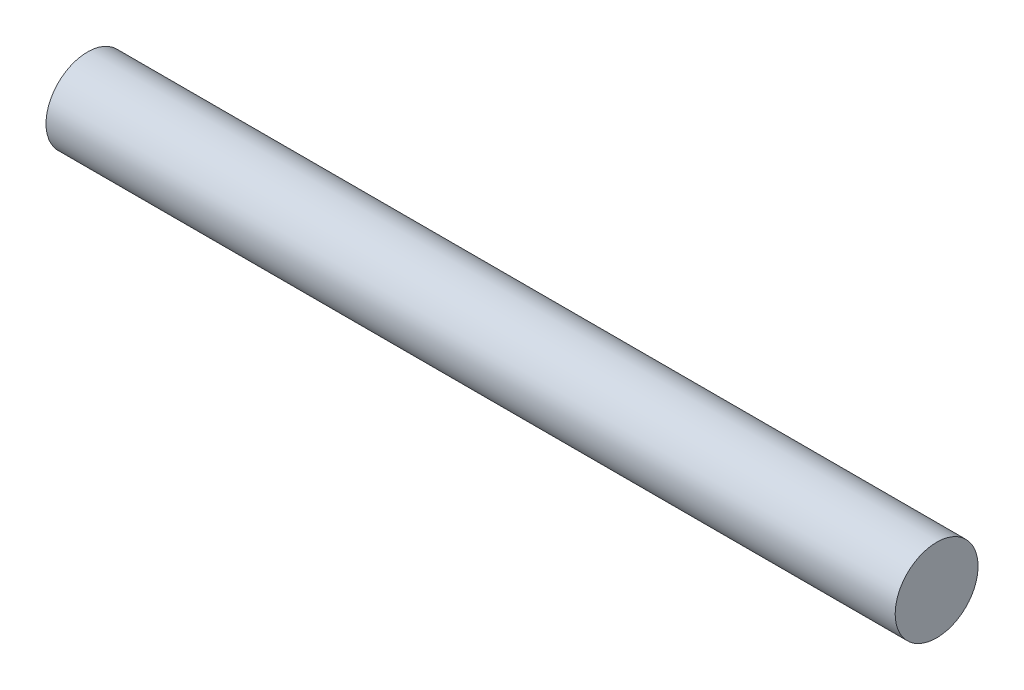
SolidWorks part; units mm, degrees
material "Stainless Steel (ferritic)"
ref_plane "Front Plane" through (0, 0, 0) normal (0, 0, 1) x (1, 0, 0)
ref_plane "Top Plane" through (0, 0, 0) normal (0, 1, 0) x (1, 0, 0)
ref_plane "Right Plane" through (0, 0, 0) normal (1, 0, 0) x (0, 0, -1)
sketch "Sketch1" plane through (0, 0, 0) normal (1, 0, 0) x (0, 0, -1)
  circle A0 centre (0, 0) radius 1.5
  dimension "D1" = 3
extrude "Boss-Extrude1" add sketch "Sketch1" along normal blind 30.73 contours A0
